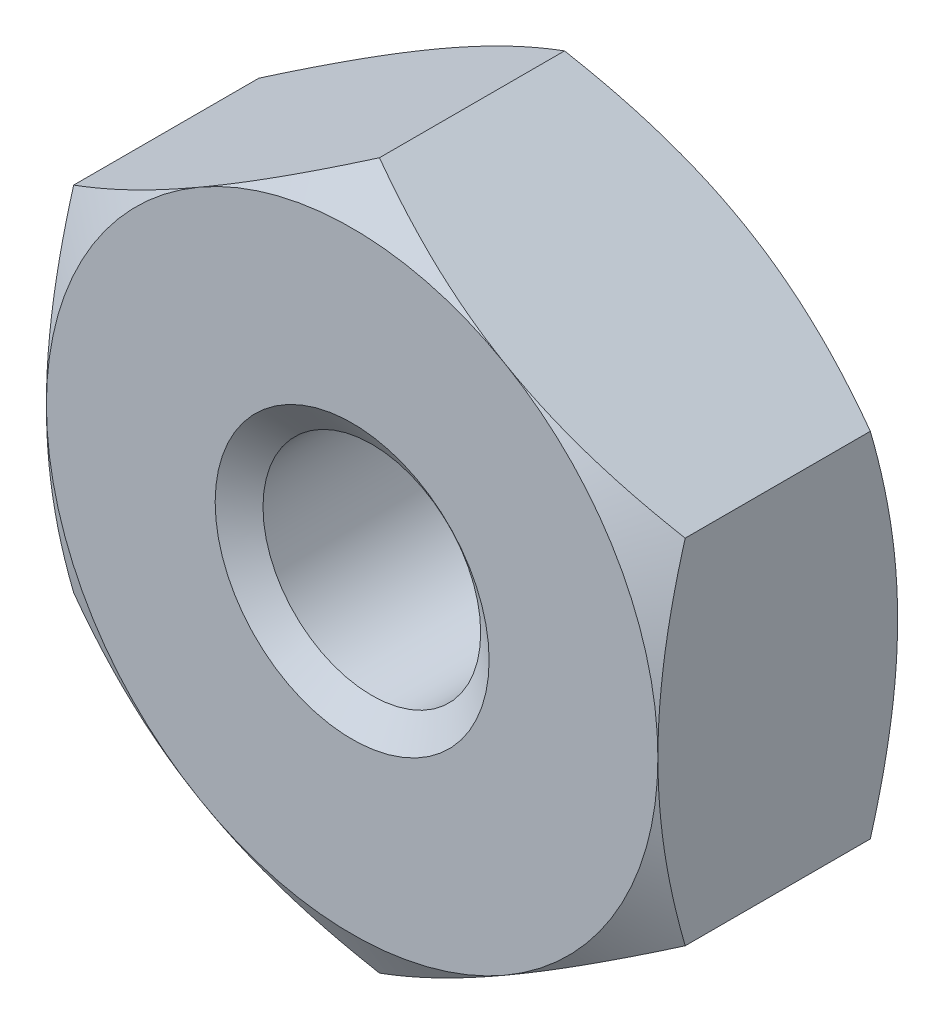
SolidWorks part; units mm, degrees
ref_plane "Plane1" through (0, 0, 0) normal (0, 0, 1) x (1, 0, 0)
ref_plane "Plane2" through (0, 0, 0) normal (0, 1, 0) x (1, 0, 0)
ref_plane "Plane3" through (0, 0, 0) normal (1, 0, 0) x (0, 0, -1)
revolve "EndChamfer" cut sketch "EndChamferSketch" angle 360 about L11
sketch "EndChamferSketch" plane through (0, 0, 0) normal (1, 0, 0) x (0, 0, -1)
  line L0 (2.4638, 1.4224) -> (2.2388, 1.1011)
  line L1 (2.5146, 1.4224) -> (2.4638, 1.4224)
  line L2 (2.5146, 1.4224) -> (2.5146, 1.1011)
  line L3 (2.5146, 1.1011) -> (2.2388, 1.1011)
  line L6 (-0.0508, 1.4224) -> (0, 1.4224)
  line L7 (0, 1.4224) -> (0.225, 1.1011)
  line L9 (0.225, 1.1011) -> (-0.0508, 1.1011)
  line L10 (-0.0508, 1.1011) -> (-0.0508, 1.4224)
  line L11 (25.0375, 0) -> (38.388, 0) construction
  dimension "D1" = 35
  dimension "D2" = 0.0508
  dimension "Offset1" = 2.5146
  dimension "ThreadMajor" = 1.4224
  dimension "ChamferDepth" = 0.3213
  dimension "Offset2" = 2.5654
extrude "BaseNut" add sketch "BaseNutSke" against normal blind 2.4892
sketch "BaseNutSke" plane through (0, 0, 0) normal (0, 0, 1) x (1, 0, 0)
  line L6 (3.175, 1.8331) -> (3.175, -1.8331)
  line L7 (-3.175, 1.8331) -> (-3.175, -1.8331)
  line L8 (3.175, 1.8331) -> (0, 3.6662)
  line L9 (0, 3.6662) -> (-3.175, 1.8331)
  line L10 (-3.175, -1.8331) -> (0, -3.6662)
  line L11 (0, -3.6662) -> (3.175, -1.8331)
  circle A0 centre (0, 0) radius 1.1303
  dimension "D4" = 3.175
  dimension "Thread_min" = 2.2606
  dimension "D1" = 120
  dimension "D2" = 3.175
  dimension "D3" = 3.175
  dimension "Width_flats" = 6.35
cosmetic thread "ThreadCosmetic" parameters "Thread_nominal"=2.8448
sketch "Sketch3" plane through (0, 0, 0) normal (1, 0, 0) x (0, 0, -1)
  line L0 (2.4892, 3.175) -> (2.2056, 3.6662)
  line L1 (2.2056, 3.6662) -> (2.2056, 16.3662)
  line L2 (2.2056, 16.3662) -> (15.1892, 16.3662)
  line L3 (15.1892, 16.3662) -> (15.1892, 3.175)
  line L4 (15.1892, 3.175) -> (2.4892, 3.175)
  line L5 (2.4892, 1.8331) -> (2.4892, 3.6662) construction
  line L6 (2.4892, 3.6662) -> (0, 3.6662) construction
  line L7 (0, 0) -> (38.6776, 0) construction
  line L8 (2.4892, 0) -> (0, 0) construction
  line L9 (1.2446, 3.6662) -> (1.2446, 44.222) construction
  line L10 (0.2836, 16.3662) -> (-12.7, 16.3662)
  line L11 (-12.7, 16.3662) -> (-12.7, 3.175)
  line L12 (-12.7, 3.175) -> (0, 3.175)
  line L13 (0, 3.175) -> (0.2836, 3.6662)
  line L14 (0.2836, 3.6662) -> (0.2836, 16.3662)
  line L16 (2.4892, 3.6662) -> (0, 3.6662) construction
  dimension "D1" = 3.175
  dimension "D2" = 30
  dimension "D3" = 12.7
  dimension "D4" = 12.7
revolve "Double-Chamfer" cut sketch "Sketch3" angle 360 about L7
equation "\"D2@BaseNutSke\" = \"Width_flats@BaseNutSke\" / 2"
equation "\"D3@BaseNutSke\" = \"Width_flats@BaseNutSke\" / 2"
equation "\"D1@Sketch3\" = \"Width_flats@BaseNutSke\" /2"
equation "\"D4@BaseNutSke\" = \"D3@BaseNutSke\""
equation "' \"Num_threads@ThdSchPat\" = \"Num_threads@ThdSchPat\" - sgn( \"Num_threads@ThdSchPat\" - 1) '---chamfered tips only---"
equation "\"ThreadMajor@EndChamferSketch\" = \"Thread_nominal@ThreadCosmetic\" * 0.5"
equation "\"ChamferDepth@EndChamferSketch\" = (\"Thread_nominal@ThreadCosmetic\" - \"Thread_min@BaseNutSke\") * 0.55"
equation "\"Offset1@EndChamferSketch\" = \"Thickness@BaseNut\" + 0.001"
equation "\"Offset2@EndChamferSketch\" = \"Offset1@EndChamferSketch\" + 0.002"
